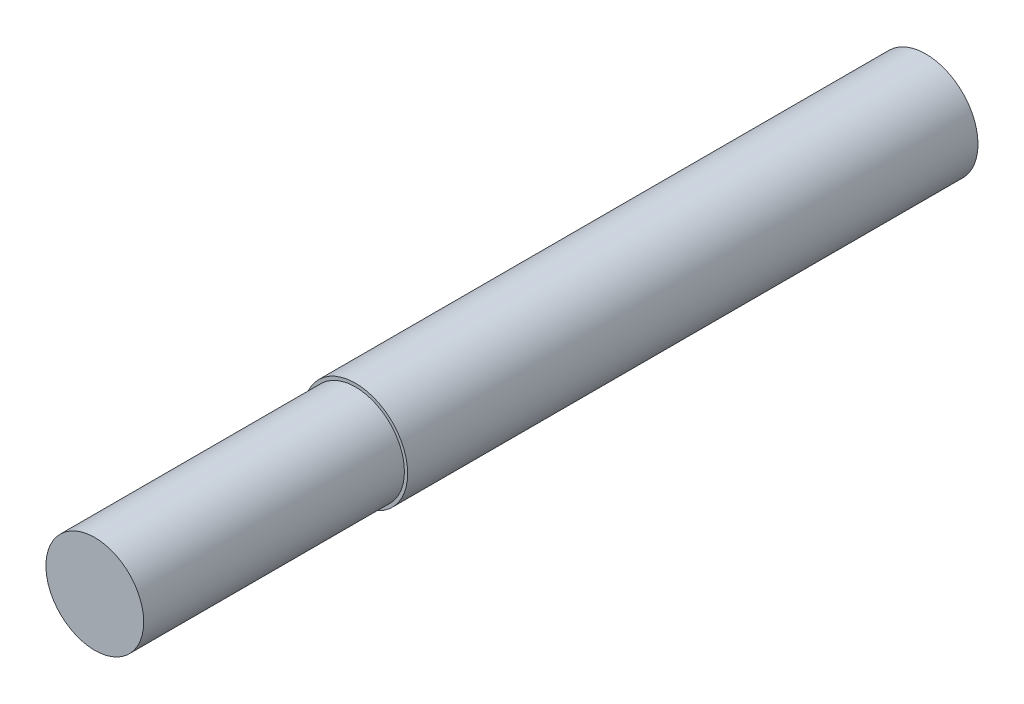
SolidWorks part; units mm, degrees
material "Латунь"
ref_plane "Front Plane" through (0, 0, 0) normal (0, 0, 1) x (1, 0, 0)
ref_plane "Top Plane" through (0, 0, 0) normal (0, 1, 0) x (1, 0, 0)
ref_plane "Right Plane" through (0, 0, 0) normal (1, 0, 0) x (0, 0, -1)
sketch "Эскиз1" plane through (0, 0, 0) normal (0, 1, 0) x (1, 0, 0)
  line L0 (0, 0) -> (0, 27.75) construction
  line L1 (0, 0) -> (-1.5, 0)
  line L2 (-1.5, 0) -> (-1.5, 8)
  line L3 (-1.5, 8) -> (-1.6, 8)
  line L4 (-1.6, 8) -> (-1.6, 25.5)
  line L5 (-1.6, 25.5) -> (-0.75, 25.5)
  line L6 (-0.75, 25.5) -> (-0.75, 17.5)
  line L7 (-0.75, 17.5) -> (0, 17.5)
  line L8 (0, 17.5) -> (0, 0)
  dimension "D1" = 3
  dimension "D2" = 3.2
  dimension "D3" = 1.5
  dimension "D4" = 8
  dimension "D5" = 8
  dimension "D6" = 17.5
revolve "Повернуть1" add sketch "Эскиз1" angle 360 about L0
